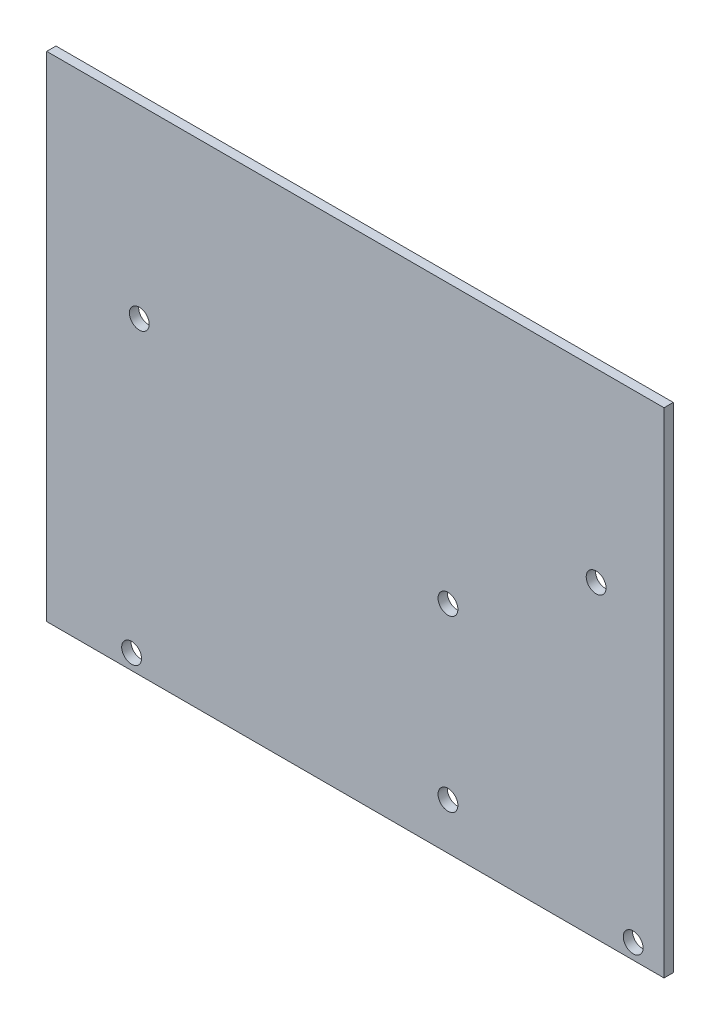
SolidWorks part; units mm, degrees
ref_plane "Front Plane" through (0, 0, 0) normal (0, 0, 1) x (1, 0, 0)
ref_plane "Top Plane" through (0, 0, 0) normal (0, 1, 0) x (1, 0, 0)
ref_plane "Right Plane" through (0, 0, 0) normal (1, 0, 0) x (0, 0, -1)
sketch "Sketch1" plane through (0, 0, 0) normal (0, 0, 1) x (1, 0, 0)
  line L1 (-50.8, -40.64) -> (50.8, -40.64)
  line L2 (-50.8, -40.64) -> (-50.8, 40.64)
  line L3 (-50.8, 40.64) -> (50.8, 40.64)
  line L4 (50.8, -40.64) -> (50.8, 40.64)
  line L5 (-50.8, -40.64) -> (50.8, 40.64) construction
  line L6 (-50.8, 40.64) -> (50.8, -40.64) construction
  point P0 (0, 0)
  dimension "D1" = 101.6
  dimension "D2" = 81.28
extrude "Boss-Extrude1" add sketch "Sketch1" along normal mid plane 1.524
hole_wizard "#4 Clearance Hole1" positions "Sketch4" profile "Sketch3" hole size "#4" standard "ANSI Inch" end condition through all
sketch "Sketch4" plane through (0, 0, 0.762) normal (0, 0, 1) x (1, 0, 0)
  line L0 (-50.8, 40.64) -> (-50.8, -40.64) construction
  line L1 (-50.8, -40.64) -> (50.8, -40.64) construction
  point P0 (-36.83, -38.1)
  point P7 (15.24, -33.02)
  point P10 (15.24, -5.08)
  point P12 (45.72, -38.1)
  point P14 (-35.56, 10.16)
  point P16 (39.624, 10.16)
  dimension "D1" = 13.97
  dimension "D2" = 2.54
  dimension "D3" = 66.04
  dimension "D4" = 7.62
  dimension "D5" = 96.52
  dimension "D6" = 35.56
  dimension "D7" = 90.424
  dimension "D8" = 50.8
  dimension "D9" = 15.24
sketch "Sketch3" plane through (-36.83, -38.1, 0.762) normal (1, 0, 0) x (0, -1, 0)
  line L0 (0, 0) -> (0, 1.524)
  line L1 (0, 1.524) -> (1.6319, 1.524)
  line L2 (1.6319, 1.524) -> (1.6319, 0)
  line L5 (1.6319, 0) -> (0, 0)
  line L11 (0, -6.35) -> (0, 107.95) construction
  dimension "Thru Hole Dia." = 3.2639
  dimension "Thru Hole Depth" = 1.524
sketch "Sketch5" plane through (0, 0, 0.762) normal (0, 0, 1) x (1, 0, 0)
  line L1 (39.624, 10.16) -> (15.24, 10.16)
  line L2 (39.624, 10.16) -> (39.624, -33.02)
  line L3 (39.624, -33.02) -> (15.24, -33.02)
  line L4 (15.24, 10.16) -> (15.24, -33.02)
  line L5 (39.624, 10.16) -> (15.24, -33.02) construction
  line L6 (39.624, -33.02) -> (15.24, 10.16) construction
  point P0 (15.24, -5.08)
  point P6 (27.432, -11.43)
  dimension "D1" = 24.384
  dimension "D2" = 43.18
  dimension "D3" = 15.24
